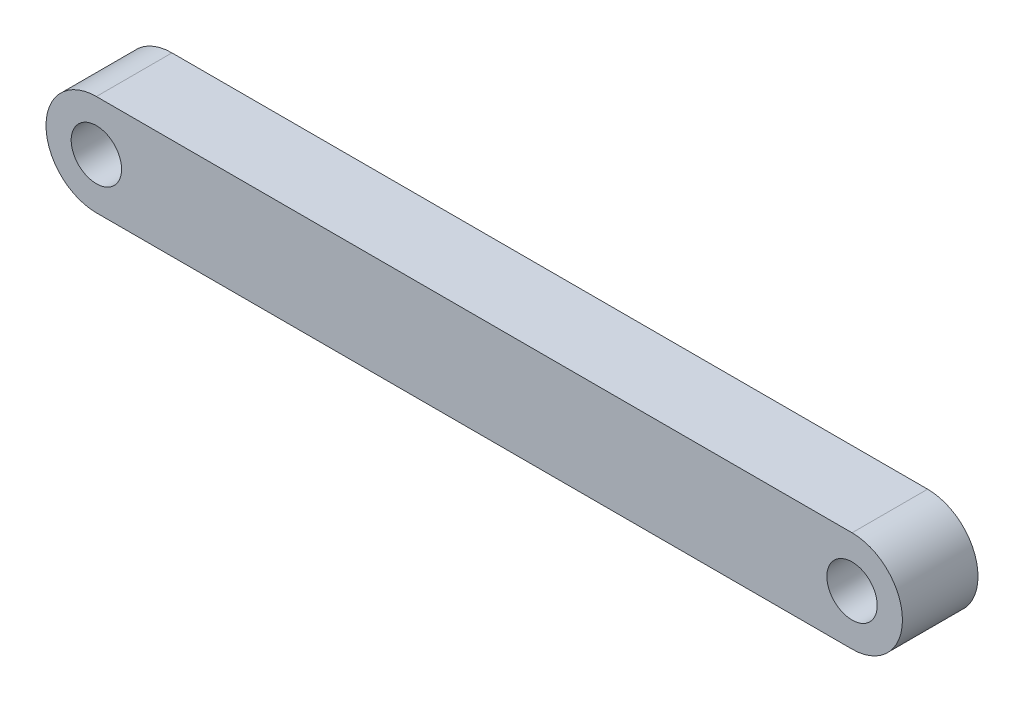
SolidWorks part; units mm, degrees
ref_plane "Plan de face" through (0, 0, 0) normal (0, 0, 1) x (1, 0, 0)
ref_plane "Plan de dessus" through (0, 0, 0) normal (0, 1, 0) x (1, 0, 0)
ref_plane "Plan de droite" through (0, 0, 0) normal (1, 0, 0) x (0, 0, -1)
sketch "Esquisse1" plane through (0, 0, 0) normal (0, 0, 1) x (1, 0, 0)
  line L0 (-15, 0) -> (15, 0) construction
  line L1 (-15, 2) -> (15, 2)
  line L2 (-15, -2) -> (15, -2)
  arc A0 (-15, 2) -> (-15, -2) centre (-15, 0) ccw
  arc A1 (15, -2) -> (15, 2) centre (15, 0) ccw
  circle A2 centre (-15, 0) radius 1
  circle A3 centre (15, 0) radius 1
  point P2 (0, 0)
  dimension "D2" = 2
  dimension "D3" = 2
  dimension "D4" = 2
  dimension "D1" = 30
extrude "Boss.-Extru.1" add sketch "Esquisse1" along normal blind 3
